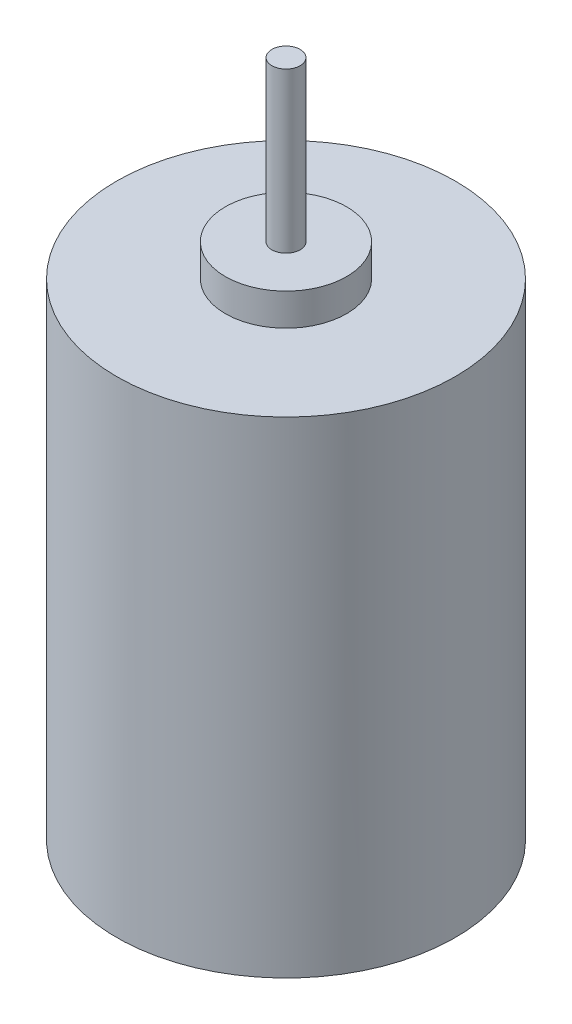
SolidWorks part; units mm, degrees
ref_plane "Front Plane" through (0, 0, 0) normal (0, 0, 1) x (1, 0, 0)
ref_plane "Top Plane" through (0, 0, 0) normal (0, 1, 0) x (1, 0, 0)
ref_plane "Right Plane" through (0, 0, 0) normal (1, 0, 0) x (0, 0, -1)
sketch "Sketch2" plane through (0, 0, 0) normal (0, 1, 0) x (1, 0, 0)
  circle A0 centre (0, 0) radius 13.7
  dimension "D1" = 27.4
extrude "Boss-Extrude1" add sketch "Sketch2" along normal blind 57 contours A0
sketch "Sketch15" plane through (0, 57, 0) normal (0, 1, 0) x (1, 0, 0)
  circle A0 centre (0, 0) radius 1.143
  dimension "D1" = 2.286
extrude "Cut-Extrude10" cut sketch "Sketch15" against normal blind 12.9 flip side to cut
sketch "Sketch18" plane through (0, 44.1, 0) normal (0, 1, 0) x (1, 0, 0)
  circle A0 centre (0, 0) radius 4.9
  dimension "D1" = 9.8
extrude "Cut-Extrude13" cut sketch "Sketch18" against normal blind 2.6 flip side to cut
sketch "Sketch21" plane through (0, 0, 0) normal (0, -1, 0) x (-1, 0, 0)
  circle A0 centre (0, 0) radius 1.1
  dimension "D1" = 2.2
extrude "Cut-Extrude16" cut sketch "Sketch21" against normal blind 1.3 flip side to cut
sketch "Sketch23" plane through (0, 0, 0) normal (0, -1, 0) x (1, 0, 0)
  circle A0 centre (0, 0) radius 4.9
  dimension "D1" = 9.8
extrude "Cut-Extrude18" cut sketch "Sketch23" against normal blind 2.2 flip side to cut
sketch "Sketch34" plane through (0, 0, 0) normal (0, -1, 0) x (-1, 0, 0)
  point P0 (0, 0)
sketch "Sketch35" plane through (0, 41.5, 0) normal (0, 1, 0) x (1, 0, 0)
  line L0 (-8, 0) -> (8, 0) construction
  circle A0 centre (0, 0) radius 8
  dimension "D1" = 16
sketch "Sketch36" plane through (0, 41.5, 0) normal (0, 1, 0) x (1, 0, 0)
  circle A0 centre (92.499, 0.4577) radius 1
  circle A1 centre (108.499, 0.4577) radius 1
  dimension "D1" = 2
equation "\"MDF\"= 4.8mm"
equation "\"Foamcore\"= 4.6mm"
equation "\"PCB\" = 1.6mm"
equation "\"GMaterial\"= \"MDF\""
equation "\"BaseWidth\" = 10in"
equation "\"SkidLength\" = 1in"
equation "\"SkidClearance\" = 0.4in"
equation "\"MotorMountLength\" = 2in"
equation "\"MotorMountWidth\" = \"GMaterial\""
equation "\"MotorMountHeight\" = 2.25in"
equation "\"UnoStackWidth\" = 77.4mm"
equation "\"UnoStackLength\" = 79.8mm"
equation "\"UnoStackHeight\" = 34.2mm"
equation "\"TallHexRiserHeight\" = 22.2mm"
equation "\"PingPongBallSize\" = 40mm"
equation "\"BarrelLength\" = 9in"
equation "\"BarrelSize\" = \"PingPongBallSize\""
equation "\"PlatformLength\" = 4in"
equation "\"PlatformWidth\" = 6in"
equation "\"WheelDiameter\"=2.99213"
equation "\"ServoMountHeight\"=2.49223"
equation "\"ServoGearHeight\" = 0.95330261in"
equation "\"ServoMountLength\"= 1.53774"
equation "\"PivotHoleRadius\"= 0.616358"
equation "\"PlatformMountHeight\" = 3.19"
equation "\"TensionOffSet\"= .3mm"
equation "\"MotorMountWedge\"=0.333333"
equation "\"LaserCutterOffset\"= .3mm"
equation "\"BumperWidth\"=11"
equation "\"PitchingWheelBoltShoulder\" = 4.5mm"
equation "\"BrassCouplingLength\" = 18mm"
equation "\"PitcherWheelCompression\" = 2.5mm"
equation "\"PitchingMotorHeight\" = 57.0mm"
equation "\"PitchingMotorShaftTopHeight\" = \"PitchingMotorHeight\" - 44.1mm"
equation "\"PitchingMotorTopShoulderHeight\" = 40.6mm - \"PitchingMotorBodyHeight\" "
equation "\"PitchingMotorBodyHeight\" = 38mm"
equation "\"PitchingMotorBottomShoulderHeight\" = 40.2mm - \"PitchingMotorBodyHeight\""
equation "\"PitchingMotorBottomShaftHeight\" = \"PitchingMotorHeight\" - \"PitchingMotorShaftTopHeight\" - \"PitchingMotorTopShoulderHeight\" - \"PitchingMotorBodyHeight\" - \"PitchingMotorBottomShoulderHeight\""
equation "\"PitchingMotorShaftDiameter\" = 2.2mm"
equation "\"PitchingMotorBodyDiameter\" = 27.4mm"
equation "\"PitchingMotorTopShoulderDiameter\" = 9.8mm"
equation "\"PitchingMotorBottomShoulderDiameter\" = 9.8mm"
equation "\"D1@Sketch2\"=\"PitchingMotorBodyDiameter\""
equation "\"D1@Boss-Extrude1\"=\"PitchingMotorHeight\""
equation "\"D1@Cut-Extrude10\"=\"PitchingMotorShaftTopHeight\""
equation "\"D1@Sketch18\"=\"PitchingMotorTopShoulderDiameter\""
equation "\"D1@Cut-Extrude13\"=\"PitchingMotorTopShoulderHeight\""
equation "\"D1@Sketch21\"=\"PitchingMotorShaftDiameter\""
equation "\"D1@Cut-Extrude16\"=\"PitchingMotorBottomShaftHeight\""
equation "\"D1@Sketch23\"=\"PitchingMotorBottomShoulderDiameter\""
equation "\"D1@Cut-Extrude18\"=\"PitchingMotorBottomShoulderHeight\""
equation "\"PitchingWheelWidth\" = 26.2mm"
equation "\"PitchingWheelDiameter\" = 65.5mm"
equation "\"PitchingWheelMountOffset\" = 8.4mm"
equation "\"PitchingWheelInnerDiameter\" = 45.5mm"
equation "\"BrassCouplingHexSize\" = 12mm"
equation "\"BrassCouplingBoreSize\" = 3.17mm"
equation "\"PitchingMotorMountingHoleDistance\" = 16mm"
equation "\"Acrylic\" = 4.4mm"
equation "\"PitchingMotorDistance\" = \"PitchingWheelDiameter\" + \"PingPongBallSize\" - \"PitcherWheelCompression\"*2"
equation "\"D1@Sketch35\"=\"PitchingMotorMountingHoleDistance\""
